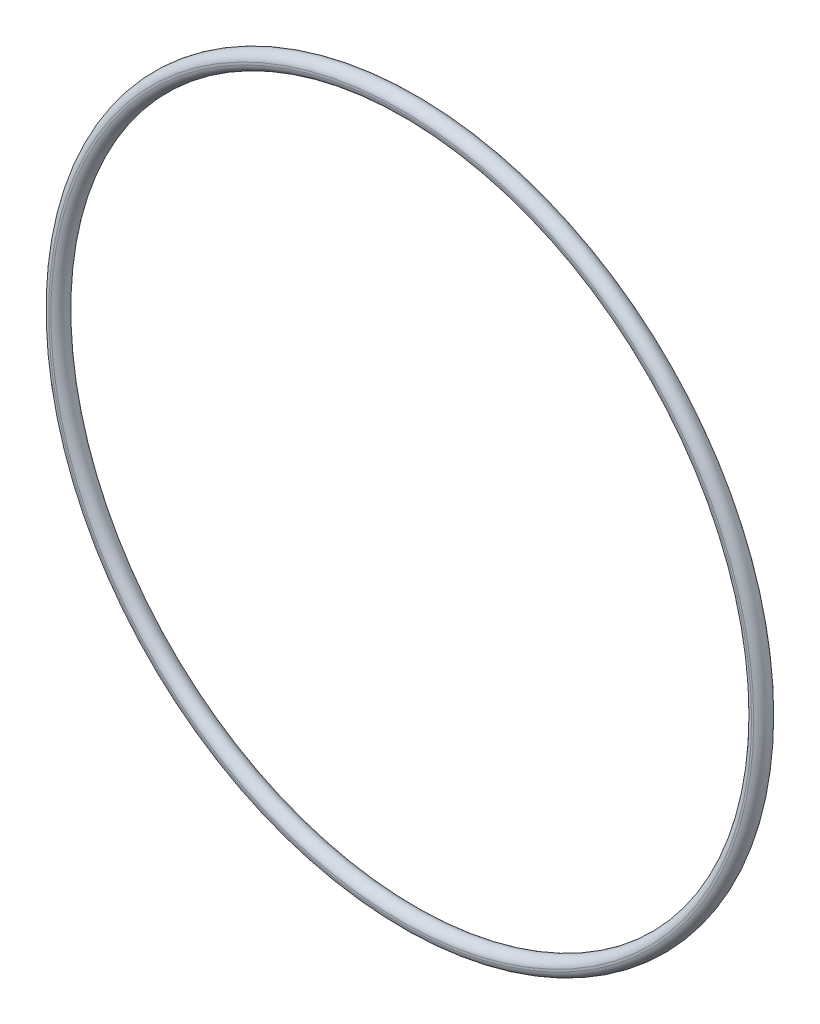
SolidWorks part; units mm, degrees
ref_plane "Front" through (0, 0, 0) normal (0, 0, 1) x (1, 0, 0)
ref_plane "Top" through (0, 0, 0) normal (0, 1, 0) x (1, 0, 0)
ref_plane "Right" through (0, 0, 0) normal (1, 0, 0) x (0, 0, -1)
sketch "Sketch1" plane through (0, 0, 0) normal (1, 0, 0) x (0, -1, 0)
  line L0 (0, -2.667) -> (0, 2.667) construction
  line L2 (-55, 0) -> (55, 0) construction
  line L3 (-104.4575, 0) -> (104.4575, 0) construction
  line L4 (106.787, -2.6456) -> (107.462, -2.6456)
  line L5 (106.787, -2.6456) -> (106.787, 2.6456)
  line L6 (106.787, 2.6456) -> (107.462, 2.6456)
  line L7 (107.462, -2.6456) -> (107.462, 2.6456)
  line L8 (106.787, -2.6456) -> (107.462, 2.6456) construction
  line L9 (106.787, 2.6456) -> (107.462, -2.6456) construction
  circle A0 centre (107.1245, 0) radius 2.667
  point P9 (104.4575, 0)
  point P10 (109.7915, 0)
  point P13 (107.1245, 2.667)
  point P14 (107.1245, -2.667)
  dimension "Width" = 5.334
  dimension "ID" = 208.915
revolve "Revolve1" add sketch "Sketch1" angle 360 about L0
